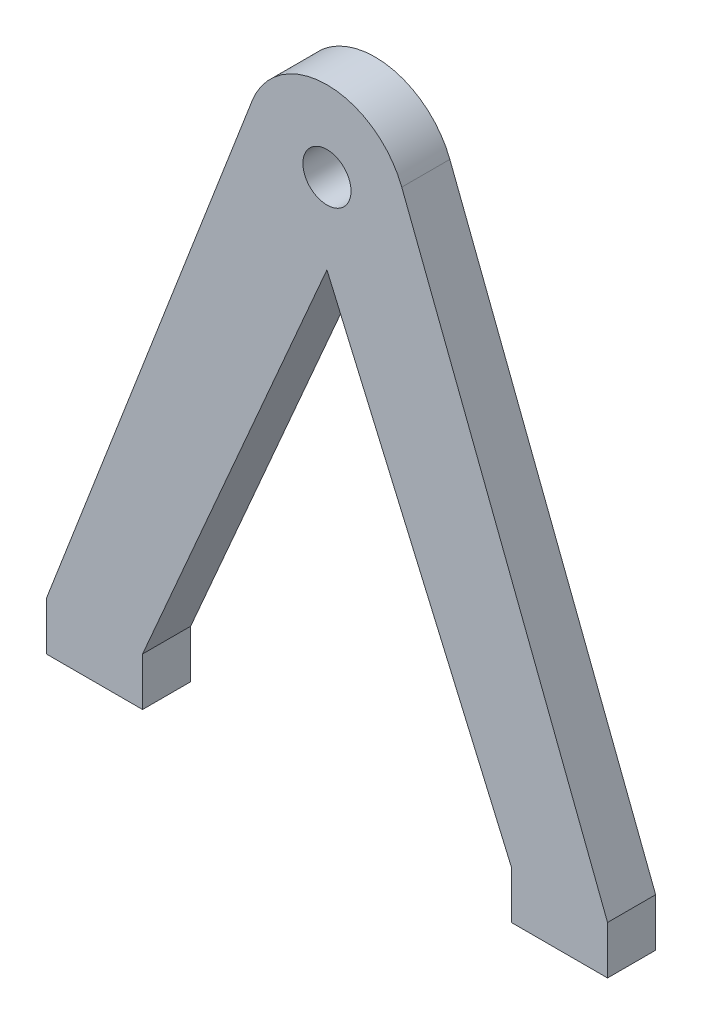
SolidWorks part; units mm, degrees
ref_plane "Plano frontal" through (0, 0, 0) normal (0, 0, 1) x (1, 0, 0)
ref_plane "Plano superior" through (0, 0, 0) normal (0, 1, 0) x (1, 0, 0)
ref_plane "Plano direito" through (0, 0, 0) normal (1, 0, 0) x (0, 0, -1)
sketch "Esboço1" plane through (0, 0, 0) normal (0, 0, 1) x (1, 0, 0)
  line L0 (0, 6) -> (25.6691, 72.5965)
  line L1 (0, 0) -> (12, 0)
  line L2 (0, 0) -> (0, 6)
  line L3 (0, 6) -> (12, 6)
  line L4 (12, 0) -> (12, 6)
  line L5 (12, 6) -> (35, 59)
  line L6 (58, 6) -> (35, 59)
  line L7 (58, 0) -> (70, 0)
  line L8 (58, 0) -> (58, 6)
  line L9 (58, 6) -> (70, 6)
  line L10 (70, 0) -> (70, 6)
  line L11 (44.3309, 72.5965) -> (70, 6)
  circle A0 centre (35, 69) radius 5
  arc A1 (25.6691, 72.5965) -> (44.3309, 72.5965) centre (35, 69) cw
  dimension "D1" = 12
  dimension "D9" = 10
  dimension "D2" = 12
  dimension "D3" = 6
  dimension "D4" = 6
  dimension "D5" = 10
  dimension "D6" = 10
  dimension "D7" = 70
  dimension "D8" = 63
extrude "Ressalto-extrusão1" add sketch "Esboço1" along normal blind 6 contours A1 L0 L3 L5 L6 L9 L11 A0 | L1 L4 L3 L2 | L7 L10 L9 L8
sketch "Esboço2" plane through (0, 0, 6) normal (0, 0, 1) x (1, 0, 0)
  line L0 (30, 69) -> (40, 69) construction
  circle A0 centre (35, 69) radius 5 construction
  circle A1 centre (35, 69) radius 5
  circle A2 centre (35, 69) radius 3
  dimension "D1" = 6
  dimension "D2" = 10
extrude "Ressalto-extrusão2" add sketch "Esboço2" against normal blind 6
